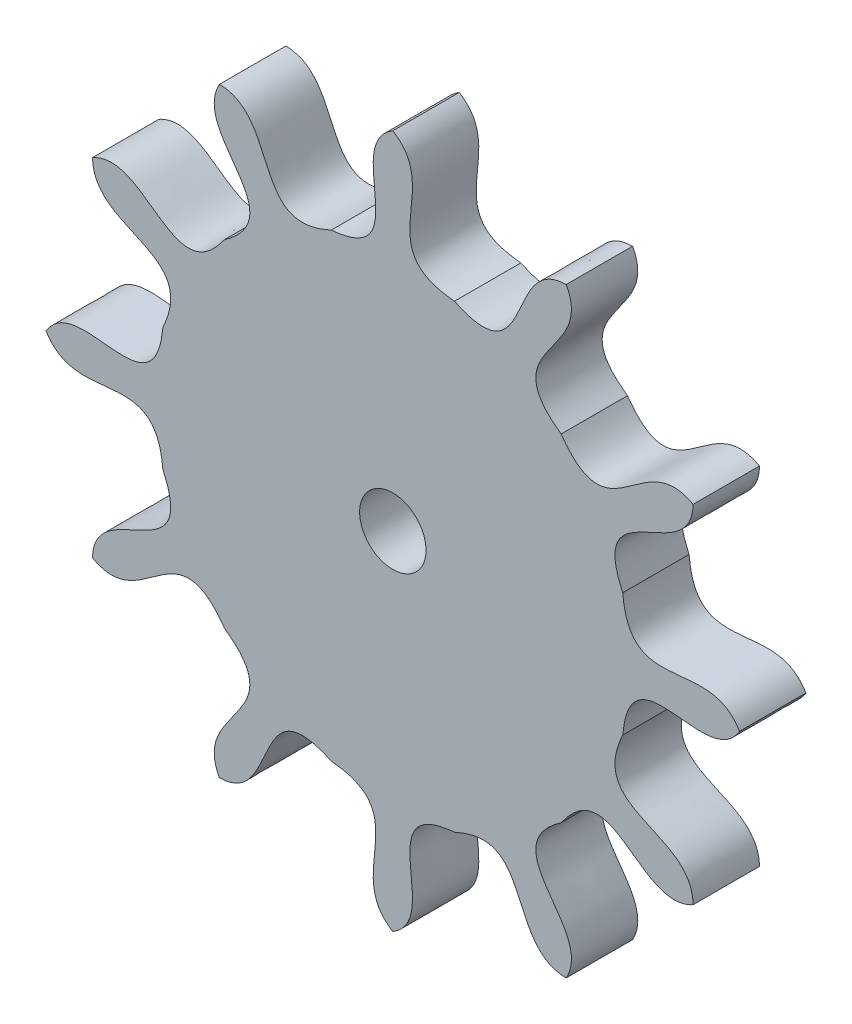
SolidWorks part; units mm, degrees
ref_plane "Front Plane" through (0, 0, 0) normal (0, 0, 1) x (1, 0, 0)
ref_plane "Top Plane" through (0, 0, 0) normal (0, 1, 0) x (1, 0, 0)
ref_plane "Right Plane" through (0, 0, 0) normal (1, 0, 0) x (0, 0, -1)
sketch "Sketch9" plane through (0, 0, 0) normal (0, 0, 1) x (1, 0, 0)
  line L0 (0, 0) -> (0, 26.1244) construction
  line L1 (-7, 26.1244) -> (7, 26.1244) construction
  line L2 (7, 26.1244) -> (19.1244, 19.1244) construction
  line L3 (19.1244, 19.1244) -> (26.1244, 7) construction
  line L4 (26.1244, 7) -> (26.1244, -7) construction
  line L5 (26.1244, -7) -> (19.1244, -19.1244) construction
  line L6 (19.1244, -19.1244) -> (7, -26.1244) construction
  line L7 (7, -26.1244) -> (-7, -26.1244) construction
  line L8 (-7, -26.1244) -> (-19.1244, -19.1244) construction
  line L9 (-19.1244, -19.1244) -> (-26.1244, -7) construction
  line L10 (-26.1244, -7) -> (-26.1244, 7) construction
  line L11 (-26.1244, 7) -> (-19.1244, 19.1244) construction
  line L12 (-19.1244, 19.1244) -> (-7, 26.1244) construction
  line L13 (-1.4, 24.1244) -> (1.4, 24.1244) construction
  line L14 (0, 0) -> (7, 26.1244) construction
  spline S0 degree 3 poles (0, 26.1244) (3.8849, 23.7886) (-1.9125, 17.9039) (4.6413, 17.3214) knots 0 0 0 0 1 1 1 1
  spline S1 degree 3 poles (0, 26.1244) (-3.8849, 23.7886) (1.9125, 17.9039) (-4.6413, 17.3214) knots 0 0 0 0 1 1 1 1
  spline S2 degree 3 poles (13.0622, 22.6244) (8.5299, 22.5439) (10.6082, 14.549) (4.6413, 17.3214) knots 0 0 0 0 1 1 1 1
  spline S3 degree 3 poles (13.0622, 22.6244) (15.2587, 18.6591) (7.2957, 16.4615) (12.6801, 12.6801) knots 0 0 0 0 1 1 1 1
  spline S4 degree 3 poles (22.6244, 13.0622) (18.6591, 15.2587) (16.4615, 7.2957) (12.6801, 12.6801) knots 0 0 0 0 1 1 1 1
  spline S5 degree 3 poles (22.6244, 13.0622) (22.5439, 8.5299) (14.549, 10.6082) (17.3214, 4.6413) knots 0 0 0 0 1 1 1 1
  spline S6 degree 3 poles (26.1244, 0) (23.7886, 3.8849) (17.9039, -1.9125) (17.3214, 4.6413) knots 0 0 0 0 1 1 1 1
  spline S7 degree 3 poles (26.1244, 0) (23.7886, -3.8849) (17.9039, 1.9125) (17.3214, -4.6413) knots 0 0 0 0 1 1 1 1
  spline S8 degree 3 poles (22.6244, -13.0622) (22.5439, -8.5299) (14.549, -10.6082) (17.3214, -4.6413) knots 0 0 0 0 1 1 1 1
  spline S9 degree 3 poles (22.6244, -13.0622) (18.6591, -15.2587) (16.4615, -7.2957) (12.6801, -12.6801) knots 0 0 0 0 1 1 1 1
  spline S10 degree 3 poles (13.0622, -22.6244) (15.2587, -18.6591) (7.2957, -16.4615) (12.6801, -12.6801) knots 0 0 0 0 1 1 1 1
  spline S11 degree 3 poles (13.0622, -22.6244) (8.5299, -22.5439) (10.6082, -14.549) (4.6413, -17.3214) knots 0 0 0 0 1 1 1 1
  spline S12 degree 3 poles (0, -26.1244) (3.8849, -23.7886) (-1.9125, -17.9039) (4.6413, -17.3214) knots 0 0 0 0 1 1 1 1
  spline S13 degree 3 poles (0, -26.1244) (-3.8849, -23.7886) (1.9125, -17.9039) (-4.6413, -17.3214) knots 0 0 0 0 1 1 1 1
  spline S14 degree 3 poles (-13.0622, -22.6244) (-8.5299, -22.5439) (-10.6082, -14.549) (-4.6413, -17.3214) knots 0 0 0 0 1 1 1 1
  spline S15 degree 3 poles (-13.0622, -22.6244) (-15.2587, -18.6591) (-7.2957, -16.4615) (-12.6801, -12.6801) knots 0 0 0 0 1 1 1 1
  spline S16 degree 3 poles (-22.6244, -13.0622) (-18.6591, -15.2587) (-16.4615, -7.2957) (-12.6801, -12.6801) knots 0 0 0 0 1 1 1 1
  spline S17 degree 3 poles (-22.6244, -13.0622) (-22.5439, -8.5299) (-14.549, -10.6082) (-17.3214, -4.6413) knots 0 0 0 0 1 1 1 1
  spline S18 degree 3 poles (-26.1244, 0) (-23.7886, -3.8849) (-17.9039, 1.9125) (-17.3214, -4.6413) knots 0 0 0 0 1 1 1 1
  spline S19 degree 3 poles (-26.1244, 0) (-23.7886, 3.8849) (-17.9039, -1.9125) (-17.3214, 4.6413) knots 0 0 0 0 1 1 1 1
  spline S20 degree 3 poles (-22.6244, 13.0622) (-22.5439, 8.5299) (-14.549, 10.6082) (-17.3214, 4.6413) knots 0 0 0 0 1 1 1 1
  spline S21 degree 3 poles (-22.6244, 13.0622) (-18.6591, 15.2587) (-16.4615, 7.2957) (-12.6801, 12.6801) knots 0 0 0 0 1 1 1 1
  spline S22 degree 3 poles (-13.0622, 22.6244) (-15.2587, 18.6591) (-7.2957, 16.4615) (-12.6801, 12.6801) knots 0 0 0 0 1 1 1 1
  spline S23 degree 3 poles (-13.0622, 22.6244) (-8.5299, 22.5439) (-10.6082, 14.549) (-4.6413, 17.3214) knots 0 0 0 0 1 1 1 1
  point P6 (0, 26.1244)
  point P11 (0, 24.1244)
  dimension "D1" = 26.1244
  dimension "D2" = 14
  dimension "D4" = 2.8
  dimension "D5" = 2
  dimension "D3" = 12
extrude "Boss-Extrude4" add sketch "Sketch9" along normal blind 5
sketch "Sketch10" plane through (0, 0, 5) normal (0, 0, 1) x (1, 0, 0)
  circle A0 centre (0, 0) radius 2.5
  dimension "D1" = 5
extrude "Cut-Extrude3" cut sketch "Sketch10" against normal blind 5
equation "\"n\"= 12'# stranica"
equation "\"s\"= 1.4cm'duljina stranice"
equation "\"r\"= \"s\" / ( 2 * sin ( pi / \"n\" ) )'radius"
equation "\"pinTopLen\"= 0.1cm"
equation "\"pinTopWidth\"= 0.2"
equation "\"a\"= \"r\" * cos ( pi / \"n\" )'apothem (from center to mid point)"
equation "\"interiorAngle\"= 180 - 360 / \"n\""
equation "\"D2@Sketch9\"= \"s\""
